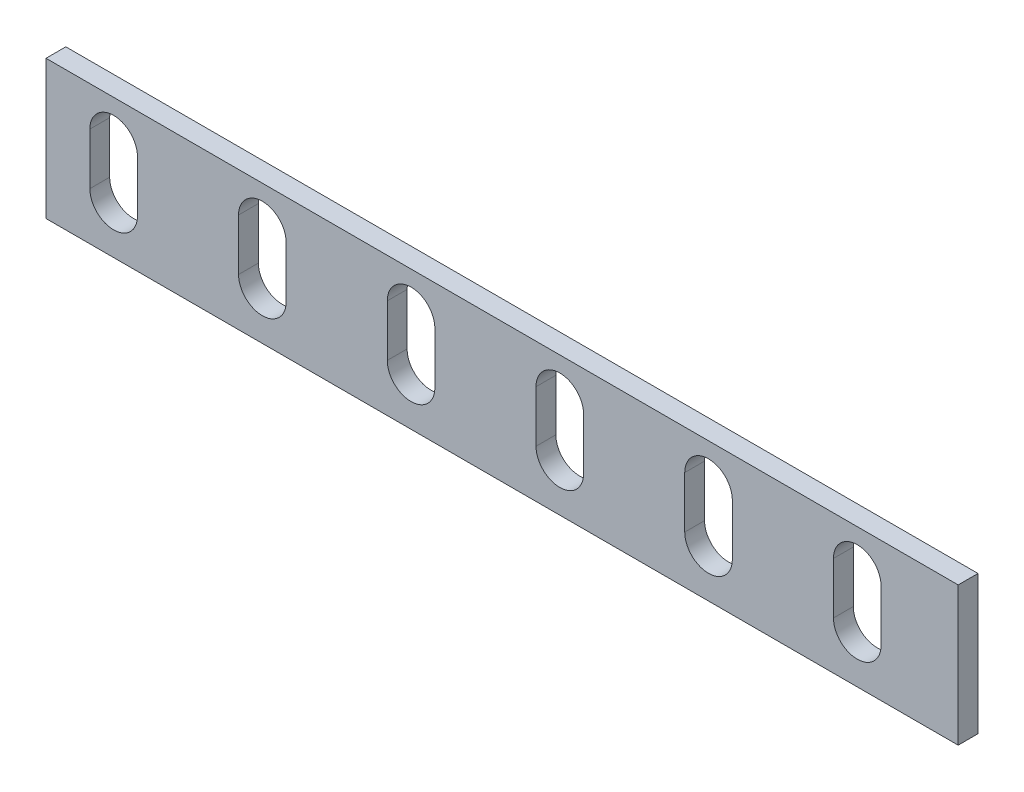
SolidWorks part; units mm, degrees
ref_plane "Front Plane" through (0, 0, 0) normal (0, 0, 1) x (1, 0, 0)
ref_plane "Top Plane" through (0, 0, 0) normal (0, 1, 0) x (1, 0, 0)
ref_plane "Right Plane" through (0, 0, 0) normal (1, 0, 0) x (0, 0, -1)
sketch "Sketch1" plane through (0, 0, 0) normal (0, 0, 1) x (1, 0, 0)
  line L0 (-382.162, 72.7411) -> (-382.162, 20.7411) construction
  line L1 (-450.3739, 112.521) -> (469.6261, 112.521)
  line L2 (-450.3739, 112.521) -> (-450.3739, -27.479)
  line L3 (-450.3739, -27.479) -> (469.6261, -27.479)
  line L4 (469.6261, 112.521) -> (469.6261, -27.479)
  line L9 (-358.162, 72.7411) -> (-358.162, 20.7411)
  line L10 (-406.162, 72.7411) -> (-406.162, 20.7411)
  line L15 (-232.162, 72.7411) -> (-232.162, 20.7411) construction
  line L16 (-208.162, 72.7411) -> (-208.162, 20.7411)
  line L21 (-256.162, 72.7411) -> (-256.162, 20.7411)
  line L22 (-82.162, 72.7411) -> (-82.162, 20.7411) construction
  line L23 (-58.162, 72.7411) -> (-58.162, 20.7411)
  line L24 (-106.162, 72.7411) -> (-106.162, 20.7411)
  line L25 (67.838, 72.7411) -> (67.838, 20.7411) construction
  line L26 (91.838, 72.7411) -> (91.838, 20.7411)
  line L27 (43.838, 72.7411) -> (43.838, 20.7411)
  line L28 (217.838, 72.7411) -> (217.838, 20.7411) construction
  line L29 (241.838, 72.7411) -> (241.838, 20.7411)
  line L30 (193.838, 72.7411) -> (193.838, 20.7411)
  line L31 (367.838, 72.7411) -> (367.838, 20.7411) construction
  line L32 (391.838, 72.7411) -> (391.838, 20.7411)
  line L33 (343.838, 72.7411) -> (343.838, 20.7411)
  arc A0 (-358.162, 72.7411) -> (-406.162, 72.7411) centre (-382.162, 72.7411) ccw
  arc A1 (-406.162, 20.7411) -> (-358.162, 20.7411) centre (-382.162, 20.7411) ccw
  arc A2 (-208.162, 72.7411) -> (-256.162, 72.7411) centre (-232.162, 72.7411) ccw
  arc A3 (-256.162, 20.7411) -> (-208.162, 20.7411) centre (-232.162, 20.7411) ccw
  arc A4 (-58.162, 72.7411) -> (-106.162, 72.7411) centre (-82.162, 72.7411) ccw
  arc A5 (-106.162, 20.7411) -> (-58.162, 20.7411) centre (-82.162, 20.7411) ccw
  arc A6 (91.838, 72.7411) -> (43.838, 72.7411) centre (67.838, 72.7411) ccw
  arc A7 (43.838, 20.7411) -> (91.838, 20.7411) centre (67.838, 20.7411) ccw
  arc A8 (241.838, 72.7411) -> (193.838, 72.7411) centre (217.838, 72.7411) ccw
  arc A9 (193.838, 20.7411) -> (241.838, 20.7411) centre (217.838, 20.7411) ccw
  arc A10 (391.838, 72.7411) -> (343.838, 72.7411) centre (367.838, 72.7411) ccw
  arc A11 (343.838, 20.7411) -> (391.838, 20.7411) centre (367.838, 20.7411) ccw
  point P6 (-382.162, 46.7411)
  point P15 (-232.162, 46.7411)
  point P22 (-82.162, 46.7411)
  point P29 (67.838, 46.7411)
  point P36 (217.838, 46.7411)
  point P43 (367.838, 46.7411)
  dimension "D1" = 920
  dimension "D2" = 140
  dimension "D3" = 48
  dimension "D4" = 52
  dimension "D5" = 6
extrude "Boss-Extrude1" add sketch "Sketch1" along normal blind 20
